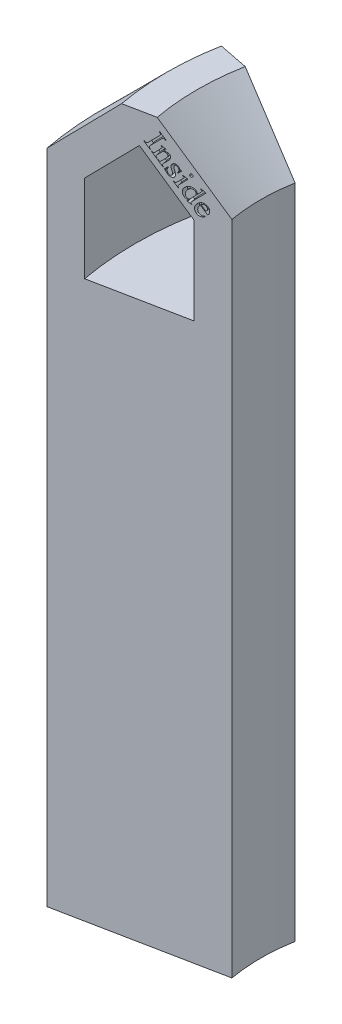
SolidWorks part; units mm, degrees
ref_plane "Front Plane" through (0, 0, 0) normal (0, 0, 1) x (1, 0, 0)
ref_plane "Top Plane" through (0, 0, 0) normal (0, 1, 0) x (1, 0, 0)
ref_plane "Right Plane" through (0, 0, 0) normal (1, 0, 0) x (0, 0, -1)
sketch "Sketch1" plane through (0, 0, 0) normal (0, 1, 0) x (1, 0, 0)
  line L0 (-39.0495, 7.7674) -> (-20.7392, 4.1253)
  line L1 (-20.7392, -4.1253) -> (-39.0495, -7.7674)
  line L2 (-20.7392, -4.1253) -> (0, 0) construction
  line L3 (0, 0) -> (-20.7392, 4.1253) construction
  line L4 (-39.8145, 0) -> (0, 0) construction
  arc A0 (-39.0495, 7.7674) -> (-39.0495, -7.7674) centre (0, 0) ccw
  arc A1 (-20.7392, 4.1253) -> (-20.7392, -4.1253) centre (0, 0) ccw
  dimension "D3" = 39.8145
  dimension "D1" = 22.5
  dimension "D2" = 18.669
extrude "Boss-Extrude1" add sketch "Sketch1" along normal blind 66.04
sketch "Sketch2" plane through (0, 0, 0) normal (0, 0, 1) x (1, 0, 0)
  line L0 (-39.8145, 66.04) -> (-39.8145, 77.9687)
  line L2 (-21.1455, 77.9687) -> (-21.1455, 66.04)
  line L3 (-39.0495, 66.04) -> (-20.7392, 66.04) construction
  line L4 (-21.1455, 66.04) -> (-24.9555, 66.04)
  line L5 (-24.9555, 66.04) -> (-24.9555, 76.3905)
  line L7 (-36.0045, 76.3905) -> (-36.0045, 66.04)
  line L8 (-36.0045, 66.04) -> (-39.8145, 66.04)
  line L9 (-30.48, 87.3032) -> (-30.48, 0) construction
  line L10 (-39.0495, 0) -> (-20.7392, 0) construction
  line L11 (-36.0045, 76.3905) -> (-30.48, 81.915)
  line L12 (-39.8145, 77.9687) -> (-32.2761, 85.5071)
  line L13 (-28.6839, 85.5071) -> (-21.1455, 77.9687)
  line L14 (-30.48, 81.915) -> (-24.9555, 76.3905)
  line L15 (-36.0045, 76.3905) -> (-24.9555, 76.3905) construction
  line L16 (-39.8145, 77.9687) -> (-21.1455, 77.9687) construction
  line L17 (-33.2422, 79.1528) -> (-35.9363, 81.8468) construction
  line L18 (-32.2761, 85.5071) -> (-28.6839, 85.5071)
  dimension "D1" = 30.48
  dimension "D2" = 15.875
  dimension "D3" = 3.81
ref_axis "Axis1" through (0, 89.7825, 0) along (0, -1, 0)
revolve "Revolve1" add sketch "Sketch2" angle 22.5 mid plane about axis through (0, 89.7825, 0) along (0, -1, 0)
sketch "Sketch3" plane through (0, 82.55, 0) normal (-0.1951, 0, -0.9808) x (0.9761, 0.098, -0.1942)
  line L0 (-8.0913, 82.1525) -> (-47.9037, 78.2313)
  line L2 (-47.7141, 78.25) -> (-29.135, 80.0799) construction
  dimension "D1" = 40.005
extrude "Cut-Extrude-Thin1" cut sketch "Sketch3" along normal mid plane 0.762 thin thin type one direction reverse wall 127
pattern_circular "CirPattern1" count 2 every 22.5 about axis through (0, 66.04, 0) along (0, -1, 0) of "Cut-Extrude-Thin1"
ref_plane "Plane2" through (-0.0743, 0, -0.3737) normal (0.1951, 0, 0.9808) x (0.9808, 0, -0.1951)
ref_plane "Plane3" through (-29.8916, -0.0002, -5.9458) normal (-0.9808, 0, -0.1951) x (-0.1951, 0, 0.9808)
sketch "Sketch4" plane through (-0.0743, 0, -0.3737) normal (0.1951, 0, 0.9808) x (0.9808, 0, -0.1951)
  line L0 (-22.7158, 75.2493) -> (-31.5705, 84.103) construction
  text T0 "Inside" font "Times New Roman" height 2.286
extrude "Cut-Extrude1" cut sketch "Sketch4" against normal blind 0.762
sketch "Sketch5" [suppressed] plane through (-0.0497, 0, -0.3777) normal (0.1305, 0, 0.9914) x (0.9914, 0, -0.1305)
  line L3 (-55.4712, 84.1048) -> (-46.2806, 74.9144) construction
  line L4 (-48.449, 76.3905) -> (-53.9737, 81.915) construction
  text T0 "Middle" font "Times New Roman" height 2.286
sketch "Sketch7" [suppressed] plane through (-0.0373, 0, -0.3792) normal (0.098, 0, 0.9952) x (0.9952, 0, -0.098)
  line L3 (-78.0023, 83.2292) -> (-69.6987, 74.9257) construction
  line L4 (-71.9445, 76.3905) -> (-77.4691, 81.915) construction
  text T0 "Outside" font "Times New Roman" height 2.286
sketch "Sketch8" plane through (0, 85.5071, 0) normal (0, 1, 0) x (1, 0, 0)
  line L0 (-31.728, 5.9226) -> (-39.122, 7.3934) construction
  line L1 (-10.1459, -1.6297) -> (9.9972, 2.377) construction
  line L2 (-30.48, 0) -> (-39.8145, 0) construction
  line L3 (-30.48, 0) -> (-21.1455, 0) construction
  circle A0 centre (-30.48, 0) radius 5.5654
  arc A1 (-39.122, 7.3934) -> (-39.122, -7.3934) centre (0, 0) ccw construction
  arc A2 (-20.8102, 3.7509) -> (-20.8102, -3.7509) centre (0, 0) ccw construction
extrude "Cut-Extrude4" [suppressed] cut sketch "Sketch5" against normal blind 0.762
extrude "Cut-Extrude5" [suppressed] cut sketch "Sketch7" against normal blind 0.762
equation "\"D1@Sketch1\"=\"angle\""
equation "\"numRep\"= 16"
equation "\"angle\"= 360 / \"numRep\""
equation "\"thick\"= 0.75"
equation "\"D2@Sketch1\"=\"thick\"-.015"
equation "\"OD\"= 1.575"
equation "\"D3@Sketch1\"=\"OD\"-.0075"
equation "\"Hwall\"=2.5"
equation "\"D1@Boss-Extrude1\"=\"Hwall\"+.1"
equation "\"D1@Sketch2\"=(\"OD\" + \"OD\" - \"thick\")/2"
equation "\"D1@Revolve1\"=\"angle\""
equation "\"D2@CirPattern1\"=\"angle\""
equation "\"D1@Sketch3\"=\"OD\""
